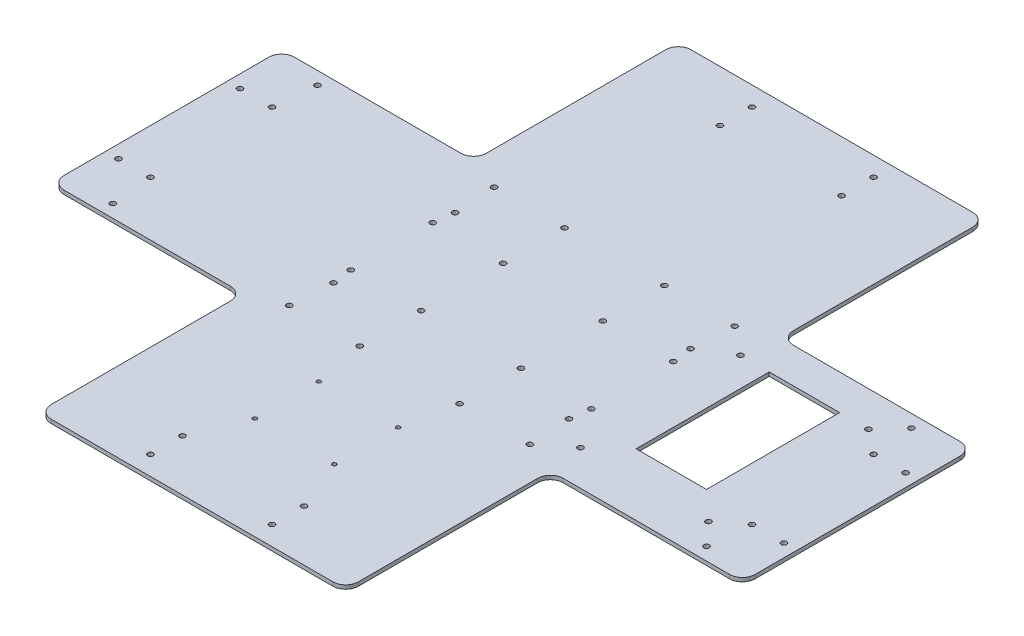
SolidWorks part; units mm, degrees
ref_plane "Front Plane" through (0, 0, 0) normal (0, 0, 1) x (1, 0, 0)
ref_plane "Top Plane" through (0, 0, 0) normal (0, 1, 0) x (1, 0, 0)
ref_plane "Right Plane" through (0, 0, 0) normal (1, 0, 0) x (0, 0, -1)
sketch "Sketch1" plane through (0, 0, 0) normal (0, 1, 0) x (1, 0, 0)
  line L0 (120, 250) -> (-120, 250)
  line L1 (-120, 250) -> (-120, 90)
  line L2 (-120, 90) -> (-270, 90)
  line L3 (-270, 90) -> (-270, -90)
  line L4 (0, 319.0603) -> (0, -214.0477) construction
  line L5 (-295.2994, 0) -> (181.6639, 0) construction
  line L6 (270, 90) -> (270, -90)
  line L7 (120, 90) -> (270, 90)
  line L8 (120, 250) -> (120, 90)
  line L9 (120, -250) -> (120, -90)
  line L10 (120, -90) -> (270, -90)
  line L11 (-120, -90) -> (-270, -90)
  line L12 (-120, -250) -> (-120, -90)
  line L13 (120, -250) -> (-120, -250)
  point P14 (0, 250)
  point P15 (-270, 0)
  point P16 (270, 0)
  point P20 (0, -250)
  dimension "D1" = 120
  dimension "D2" = 160
  dimension "150" = 150
  dimension "D3" = 90
extrude "Base" add sketch "Sketch1" along normal blind 3
fillet "Fillet1" radius 10 12 edges at (120, 1.5, -90) (270, 1.5, -90) (270, 1.5, 90) (120, 1.5, 90) (120, 1.5, 250) (-120, 1.5, 250) (-120, 1.5, 90) (-270, 1.5, 90) (-270, 1.5, -90) (-120, 1.5, -90) (-120, 1.5, -250) (120, 1.5, -250)
sketch "Sketch2" plane through (0, 3, 0) normal (0, 1, 0) x (1, 0, 0)
  line L0 (0, 268.1887) -> (0, -286.5172) construction
  line L1 (-278.1616, 0) -> (318.0529, 0) construction
  line L2 (110, 250) -> (-110, 250) construction
  line L3 (-270, 80) -> (-270, -80) construction
  circle A0 centre (-47.5, 235) radius 2.125
  circle A1 centre (-47.5, 210) radius 2.125
  circle A2 centre (-260, 47.5) radius 2.125
  circle A3 centre (-235, 47.5) radius 2.125
  circle A4 centre (-235, -47.5) radius 2.125
  circle A5 centre (-260, -47.5) radius 2.125
  circle A6 centre (260, -47.5) radius 2.125
  circle A7 centre (235, -47.5) radius 2.125
  circle A8 centre (235, 47.5) radius 2.125
  circle A9 centre (260, 47.5) radius 2.125
  circle A10 centre (47.5, 210) radius 2.125
  circle A11 centre (47.5, 235) radius 2.125
  circle A12 centre (47.5, -235) radius 2.125
  circle A13 centre (47.5, -210) radius 2.125
  circle A14 centre (-47.5, -210) radius 2.125
  circle A15 centre (-47.5, -235) radius 2.125
  dimension "D1" = 4.25
  dimension "D2" = 4.25
  dimension "D3" = 4.25
  dimension "D4" = 4.25
  dimension "D5" = 47.5
  dimension "D6" = 25
  dimension "D7" = 15
  dimension "D8" = 25
  dimension "D9" = 10
  dimension "D10" = 47.5
extrude "Armor Module Holes" cut sketch "Sketch2" against normal blind 3
sketch "Sketch3" plane through (0, 3, 0) normal (0, 1, 0) x (1, 0, 0)
  line L0 (-268.1887, 0) -> (424.969, 0) construction
  line L1 (0, 281.6655) -> (0, -321.0178) construction
  line L2 (-149.3232, 150) -> (229.1059, 150) construction
  line L3 (-149.3232, -150) -> (229.1059, -150) construction
  circle A0 centre (92, 47.5) radius 2.125
  circle A1 centre (92, -47.5) radius 2.125
  circle A2 centre (-92, -47.5) radius 2.125
  circle A3 centre (-92, 47.5) radius 2.125
  dimension "D2" = 4.25
  dimension "D1" = 150
  dimension "D3" = 47.5
  dimension "D4" = 92
extrude "Plates for Gimbal" cut sketch "Sketch3" against normal blind 3
sketch "Sketch6" plane through (0, 3, 0) normal (0, 1, 0) x (1, 0, 0)
  line L0 (-219.2229, 0) -> (231.3521, 0) construction
  line L1 (52.5596, 72.5) -> (282.564, 72.5) construction
  line L2 (52.5596, -72.5) -> (333.7759, -72.5) construction
  line L3 (92, 47.5) -> (235, 47.5) construction
  line L4 (166, 96.4976) -> (166, -82.3612) construction
  line L6 (138.5, 62.5) -> (193.5, 62.5)
  line L7 (138.5, 62.5) -> (138.5, -41.5)
  line L8 (138.5, -41.5) -> (193.5, -41.5)
  line L9 (193.5, 62.5) -> (193.5, -41.5)
  circle A2 centre (116, -62.5) radius 2.125
  circle A4 centre (216, -62.5) radius 2.125
  circle A5 centre (216, 62.5) radius 2.125
  circle A6 centre (116, 62.5) radius 2.125
  dimension "D3" = 10
  dimension "D4" = 50
  dimension "D6" = 4.25
  dimension "D1" = 72.5
  dimension "D2" = 72.5
  dimension "D9" = 74
  dimension "D12" = 55
  dimension "D13" = 27.5
  dimension "D14" = 10
  dimension "D15" = 104
extrude "Battery Mount" cut sketch "Sketch6" against normal blind 10
sketch "Sketch5" plane through (0, 3, 0) normal (0, 1, 0) x (1, 0, 0)
  line L0 (0, 63.8605) -> (0, -71.0696) construction
  line L1 (-72.0204, 0) -> (84.8823, 0) construction
  line L2 (120, -240) -> (120, -100) construction
  line L3 (-110, -250) -> (110, -250) construction
  line L4 (-158.9191, 72.5) -> (235.5165, 72.5) construction
  line L5 (193.5, 62.5) -> (138.5, 62.5) construction
  circle A0 centre (94, -32) radius 2.125
  circle A1 centre (94, -80) radius 2.125
  circle A2 centre (39, -32) radius 2.125
  circle A3 centre (39, -80) radius 2.125
  circle A4 centre (-39, -80) radius 2.125
  circle A5 centre (-39, -32) radius 2.125
  circle A6 centre (-94, -80) radius 2.125
  circle A7 centre (-94, -32) radius 2.125
  circle A8 centre (-94, 32) radius 2.125
  circle A9 centre (-94, 80) radius 2.125
  circle A10 centre (-39, 32) radius 2.125
  circle A11 centre (-39, 80) radius 2.125
  circle A12 centre (39, 80) radius 2.125
  circle A13 centre (39, 32) radius 2.125
  circle A14 centre (94, 80) radius 2.125
  circle A15 centre (94, 32) radius 2.125
  dimension "D1" = 4.25
  dimension "D2" = 4.25
  dimension "D5" = 4.25
  dimension "D6" = 4.25
  dimension "D9" = 10
  dimension "D3" = 48
  dimension "D4" = 26
  dimension "D7" = 55
  dimension "D8" = 170
extrude "Suspension Mount" cut sketch "Sketch5" against normal blind 10
sketch "Sketch7" plane through (0, 3, 0) normal (0, 1, 0) x (1, 0, 0)
  line L0 (-234.9459, 0) -> (256.0596, 0) construction
  line L1 (0, 229.7798) -> (0, -225.7367) construction
  line L2 (-120, -100) -> (-120, -240) construction
  circle A0 centre (-232, -80) radius 2.125
  circle A1 centre (-232, 80) radius 2.125
  circle A2 centre (232, 80) radius 2.125
  circle A3 centre (232, -80) radius 2.125
  dimension "D1" = 4.25
  dimension "D2" = 80
  dimension "D3" = 112
extrude "Outer Board Mount" cut sketch "Sketch7" against normal blind 10
sketch "Sketch8" plane through (0, 3, 0) normal (0, 1, 0) x (1, 0, 0)
  line L0 (0, 44.5441) -> (0, -214.63) construction
  line L1 (-110, -250) -> (110, -250) construction
  circle A0 centre (-31, -120) radius 1.575
  circle A1 centre (-31, -170) radius 1.575
  circle A2 centre (31, -170) radius 1.575
  circle A3 centre (31, -120) radius 1.575
  dimension "D1" = 3.15
  dimension "D4" = 3.15
  dimension "D2" = 31
  dimension "D3" = 130
  dimension "D5" = 31
  dimension "D6" = 80
extrude "RFID" cut sketch "Sketch8" against normal blind 10
